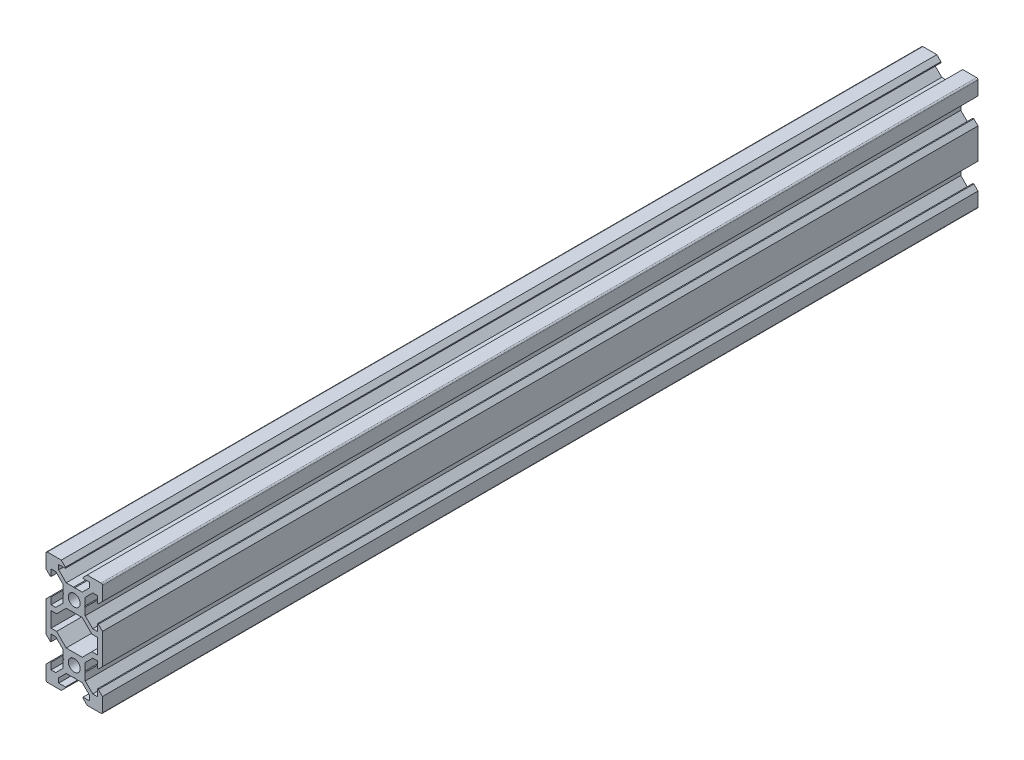
SolidWorks part; units mm, degrees
material "6061-T6 (SS)"
ref_plane "Front Plane" through (0, 0, 0) normal (0, 0, 1) x (1, 0, 0)
ref_plane "Top Plane" through (0, 0, 0) normal (0, 1, 0) x (1, 0, 0)
ref_plane "Right Plane" through (0, 0, 0) normal (1, 0, 0) x (0, 0, -1)
sketch "Sketch1" plane through (0, 0, 0) normal (0, 0, 1) x (1, 0, 0)
  line L0 (0, 0) -> (10, 0) construction
  line L1 (9.5, -20) -> (-9.5, -20)
  line L2 (10, -19.5) -> (10, 19.5)
  line L3 (9.5, 20) -> (-9.5, 20)
  line L4 (-10, -19.5) -> (-10, 19.5)
  line L5 (10, -20) -> (-10, 20) construction
  line L6 (10, 20) -> (-10, -20) construction
  circle A0 centre (0, 10) radius 2.1
  circle A1 centre (0, -10) radius 2.1
  arc A2 (-9.5, -20) -> (-10, -19.5) centre (-9.5, -19.5) cw
  arc A3 (9.5, -20) -> (10, -19.5) centre (9.5, -19.5) ccw
  arc A4 (10, 19.5) -> (9.5, 20) centre (9.5, 19.5) ccw
  arc A5 (-9.5, 20) -> (-10, 19.5) centre (-9.5, 19.5) ccw
  point P0 (0, 0)
  line B0 (0, 10) -> (0, 20) construction
  line B1 (0, 13.69) -> (-0.21, 13.9)
  line B2 (-0.21, 13.9) -> (-2.8393, 13.9)
  line B3 (-2.8393, 13.9) -> (-5.5, 16.5607)
  line B4 (-5.5, 16.5607) -> (-5.5, 18.2)
  line B5 (-5.5, 18.2) -> (-3.125, 18.2)
  line B6 (-3.125, 18.2) -> (-3.125, 18.545)
  line B7 (-3.125, 18.545) -> (-4.58, 20)
  line B8 (-4.58, 20) -> (4.58, 20)
  line B9 (0, 10) -> (-5.9132, 15.9132) construction
  line B10 (3.125, 18.545) -> (4.58, 20)
  line B11 (3.125, 18.2) -> (3.125, 18.545)
  line B12 (5.5, 18.2) -> (3.125, 18.2)
  line B13 (5.5, 16.5607) -> (5.5, 18.2)
  line B14 (2.8393, 13.9) -> (5.5, 16.5607)
  line B15 (0.21, 13.9) -> (2.8393, 13.9)
  line B16 (0, 13.69) -> (0.21, 13.9)
  line B17 (0, 10) -> (-10, 10) construction
  line B18 (-3.69, 10) -> (-3.9, 9.79)
  line B19 (-3.9, 9.79) -> (-3.9, 7.1607)
  line B20 (-3.9, 7.1607) -> (-6.5607, 4.5)
  line B21 (-6.5607, 4.5) -> (-8.2, 4.5)
  line B22 (-8.2, 4.5) -> (-8.2, 6.875)
  line B23 (-8.2, 6.875) -> (-8.545, 6.875)
  line B24 (-8.545, 6.875) -> (-10, 5.42)
  line B25 (-10, 5.42) -> (-10, 14.58)
  line B26 (0, 10) -> (-5.9132, 4.0868) construction
  line B27 (-8.545, 13.125) -> (-10, 14.58)
  line B28 (-8.2, 13.125) -> (-8.545, 13.125)
  line B29 (-8.2, 15.5) -> (-8.2, 13.125)
  line B30 (-6.5607, 15.5) -> (-8.2, 15.5)
  line B31 (-3.9, 12.8393) -> (-6.5607, 15.5)
  line B32 (-3.9, 10.21) -> (-3.9, 12.8393)
  line B33 (-3.69, 10) -> (-3.9, 10.21)
  line B34 (0, -10) -> (-10, -10) construction
  line B35 (-3.69, -10) -> (-3.9, -10.21)
  line B36 (-3.9, -10.21) -> (-3.9, -12.8393)
  line B37 (-3.9, -12.8393) -> (-6.5607, -15.5)
  line B38 (-6.5607, -15.5) -> (-8.2, -15.5)
  line B39 (-8.2, -15.5) -> (-8.2, -13.125)
  line B40 (-8.2, -13.125) -> (-8.545, -13.125)
  line B41 (-8.545, -13.125) -> (-10, -14.58)
  line B42 (-10, -14.58) -> (-10, -5.42)
  line B43 (0, -10) -> (-5.9132, -15.9132) construction
  line B44 (-8.545, -6.875) -> (-10, -5.42)
  line B45 (-8.2, -6.875) -> (-8.545, -6.875)
  line B46 (-8.2, -4.5) -> (-8.2, -6.875)
  line B47 (-6.5607, -4.5) -> (-8.2, -4.5)
  line B48 (-3.9, -7.1607) -> (-6.5607, -4.5)
  line B49 (-3.9, -9.79) -> (-3.9, -7.1607)
  line B50 (-3.69, -10) -> (-3.9, -9.79)
  line B51 (0, -10) -> (0, -20) construction
  line B52 (0, -13.69) -> (0.21, -13.9)
  line B53 (0.21, -13.9) -> (2.8393, -13.9)
  line B54 (2.8393, -13.9) -> (5.5, -16.5607)
  line B55 (5.5, -16.5607) -> (5.5, -18.2)
  line B56 (5.5, -18.2) -> (3.125, -18.2)
  line B57 (3.125, -18.2) -> (3.125, -18.545)
  line B58 (3.125, -18.545) -> (4.58, -20)
  line B59 (4.58, -20) -> (-4.58, -20)
  line B60 (0, -10) -> (5.9132, -15.9132) construction
  line B61 (-3.125, -18.545) -> (-4.58, -20)
  line B62 (-3.125, -18.2) -> (-3.125, -18.545)
  line B63 (-5.5, -18.2) -> (-3.125, -18.2)
  line B64 (-5.5, -16.5607) -> (-5.5, -18.2)
  line B65 (-2.8393, -13.9) -> (-5.5, -16.5607)
  line B66 (-0.21, -13.9) -> (-2.8393, -13.9)
  line B67 (0, -13.69) -> (-0.21, -13.9)
  line B68 (0, -10) -> (10, -10) construction
  line B69 (3.69, -10) -> (3.9, -9.79)
  line B70 (3.9, -9.79) -> (3.9, -7.1607)
  line B71 (3.9, -7.1607) -> (6.5607, -4.5)
  line B72 (6.5607, -4.5) -> (8.2, -4.5)
  line B73 (8.2, -4.5) -> (8.2, -6.875)
  line B74 (8.2, -6.875) -> (8.545, -6.875)
  line B75 (8.545, -6.875) -> (10, -5.42)
  line B76 (10, -5.42) -> (10, -14.58)
  line B77 (0, -10) -> (5.9132, -4.0868) construction
  line B78 (8.545, -13.125) -> (10, -14.58)
  line B79 (8.2, -13.125) -> (8.545, -13.125)
  line B80 (8.2, -15.5) -> (8.2, -13.125)
  line B81 (6.5607, -15.5) -> (8.2, -15.5)
  line B82 (3.9, -12.8393) -> (6.5607, -15.5)
  line B83 (3.9, -10.21) -> (3.9, -12.8393)
  line B84 (3.69, -10) -> (3.9, -10.21)
  line B85 (0, 10) -> (10, 10) construction
  line B86 (3.69, 10) -> (3.9, 10.21)
  line B87 (3.9, 10.21) -> (3.9, 12.8393)
  line B88 (3.9, 12.8393) -> (6.5607, 15.5)
  line B89 (6.5607, 15.5) -> (8.2, 15.5)
  line B90 (8.2, 15.5) -> (8.2, 13.125)
  line B91 (8.2, 13.125) -> (8.545, 13.125)
  line B92 (8.545, 13.125) -> (10, 14.58)
  line B93 (10, 14.58) -> (10, 5.42)
  line B94 (0, 10) -> (5.9132, 15.9132) construction
  line B95 (8.545, 6.875) -> (10, 5.42)
  line B96 (8.2, 6.875) -> (8.545, 6.875)
  line B97 (8.2, 4.5) -> (8.2, 6.875)
  line B98 (6.5607, 4.5) -> (8.2, 4.5)
  line B99 (3.9, 7.1607) -> (6.5607, 4.5)
  line B100 (3.9, 9.79) -> (3.9, 7.1607)
  line B101 (3.69, 10) -> (3.9, 9.79)
  line B102 (-8.2, -2.7) -> (-8.2, 2.7)
  line B103 (-8.2, 2.7) -> (-6.2393, 2.7)
  line B104 (-6.2393, 2.7) -> (-2.8393, 6.1)
  line B105 (-2.8393, 6.1) -> (2.8393, 6.1)
  line B106 (0, 6.1) -> (0, 0) construction
  line B107 (0, 0) -> (-8.2, 0) construction
  line B108 (6.2393, 2.7) -> (2.8393, 6.1)
  line B109 (8.2, 2.7) -> (6.2393, 2.7)
  line B110 (8.2, -2.7) -> (8.2, 2.7)
  line B111 (8.2, -2.7) -> (6.2393, -2.7)
  line B112 (6.2393, -2.7) -> (2.8393, -6.1)
  line B113 (-2.8393, -6.1) -> (2.8393, -6.1)
  line B114 (-6.2393, -2.7) -> (-2.8393, -6.1)
  line B115 (-8.2, -2.7) -> (-6.2393, -2.7)
  line B116 (0, 6.1) -> (0, 10) construction
  line B117 (0, 10) -> (-5.0927, 4.9073) construction
  dimension "D4" = 4.2
  dimension "D5" = 0.5
  dimension "D1" = 20
  dimension "D2" = 40
  dimension "D3" = 20
sketch_block_instance "V Slot 1-4"
sketch_block "V Slot 1" parameters "D1"=10, "D2"=11, "D3"=4.3, "D4"=1.8, "D5"=0.21, "D6"=45, "D7"=9.16, "D8"=1.5, "D9"=6.25
sketch_block_instance "V Slot 1-5"
sketch_block_instance "V Slot 1-6"
sketch_block_instance "V Slot 1-7"
sketch_block_instance "V Slot 1-8"
sketch_block_instance "V Slot 1-9"
sketch_block_instance "Center Cutout 1-1"
sketch_block "Center Cutout 1" parameters "D1"=5.4, "D2"=12.2, "D3"=8.2, "D4"=45, "D5"=10, "D6"=1.5
extrude "Boss-Extrude1" add sketch "Sketch1" along normal blind 500 contours B101 B86 B87 B88 B89 B90 B91 B92 L2 A4 L3 B10 B11 B12 B13 B14 B15 B16 B1 B2 B3 B4 B5 B6 B7 A5 L4 B27 B28 B29 B30 B31 B32 B33 B18 B19 B20 B21 B22 B23 B24 B44 B45 B46 B47 B48 B49 B50 B35
ref_plane "Upper Plane" through (0, 10, 0) normal (0, 1, 0) x (1, 0, 0)
ref_plane "Lower Plane" through (0, -10, 0) normal (0, 1, 0) x (1, 0, 0)
sketch "Sketch2" plane through (0, 0, 0) normal (0, 0, -1) x (-1, 0, 0)
  line L1 (-40.5279, 20.9489) -> (31.6716, 20.9489)
  line L2 (-40.5279, 20.9489) -> (-40.5279, -37.1058)
  line L3 (-40.5279, -37.1058) -> (31.6716, -37.1058)
  line L4 (31.6716, 20.9489) -> (31.6716, -37.1058)
extrude "Cut-Extrude2" cut sketch "Sketch2" against normal blind 189.7888
